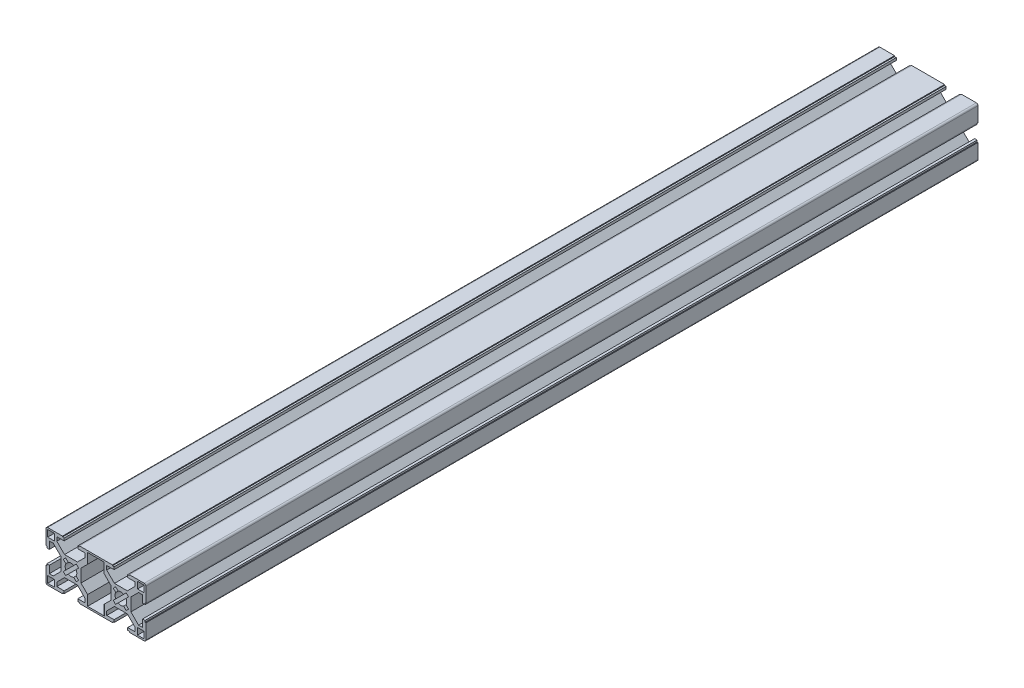
SolidWorks part; units mm, degrees
material "6063-O"
ref_plane "Plano frontal" through (0, 0, 0) normal (0, 0, 1) x (1, 0, 0)
ref_plane "Plano superior" through (0, 0, 0) normal (0, 1, 0) x (1, 0, 0)
ref_plane "Plano direito" through (0, 0, 0) normal (1, 0, 0) x (0, 0, -1)
sketch "Esboço1" plane through (0, 0, 0) normal (0, 0, 1) x (1, 0, 0)
  line L5 (0, 0) -> (-17.7944, 17.7944) construction
  line L6 (0, 3.5) -> (0, 6)
  line L8 (0, 6) -> (-3.8787, 6)
  line L9 (-3.5, 0) -> (-6, 0)
  line L48 (-6, 0) -> (-6, 3.8787)
  line L49 (-3.8787, 6) -> (-8.5, 10.6213)
  line L50 (-6, 3.8787) -> (-10.6213, 8.5)
  line L51 (0, 0) -> (-12.921, 0) construction
  line L52 (-8.5, 13) -> (-4.1, 13)
  line L53 (-4.1, 13) -> (-4.1, 14.5)
  line L54 (-4.1, 14.5) -> (-5.1, 14.5)
  line L55 (-5.1, 14.5) -> (-5.1, 15)
  line L56 (-5.1, 15) -> (-15, 15)
  line L57 (-15, 5.1) -> (-15, 15)
  line L58 (-14.5, 5.1) -> (-15, 5.1)
  line L59 (-14.5, 4.1) -> (-14.5, 5.1)
  line L60 (-13, 4.1) -> (-14.5, 4.1)
  line L61 (-13, 8.5) -> (-13, 4.1)
  line L62 (-1.6646, 3.0788) -> (-3.182, 4.5962)
  line L63 (-3.0788, 1.6646) -> (-4.5962, 3.182)
  line L64 (-4.5962, 3.182) -> (-3.182, 4.5962)
  line L65 (-8.5, 13) -> (-8.5, 10.6213)
  line L66 (-10, 14) -> (-14, 14)
  line L67 (-10, 14) -> (-10, 10)
  line L68 (-10, 10) -> (-14, 10)
  line L69 (-14, 14) -> (-14, 10)
  line L70 (-10, 14) -> (-14, 10) construction
  line L71 (-10, 10) -> (-14, 14) construction
  line L72 (-13, 8.5) -> (-10.6213, 8.5)
  circle A1 centre (0, 0) radius 3.5
  point P25 (-12, 12)
  dimension "D5" = 10.9
  dimension "D9" = 5.5
  dimension "D10" = 2
  dimension "D11" = 4
  dimension "D12" = 4
  dimension "D13" = 1
  dimension "D1" = 7
  dimension "D2" = 6
  dimension "D3" = 3
  dimension "D4" = 9.9
  dimension "D6" = 0.5
  dimension "D7" = 1.5
  dimension "D8" = 15
  dimension "D14" = 6.5
extrude "Ressalto-extrusão1" add sketch "Esboço1" along normal blind 500 contours A1 L6 L8 L49 L65 L52 L53 L54 L55 L56 L57 L58 L59 L60 L61 L72 L50 L48 L9 L63 L64 L62 L69 L66 L67 L68
sketch "Esboço3" plane through (0, 0, 0) normal (1, 0, 0) x (0, 0, -1)
  line L0 (0, 0) -> (-1000, 0) construction
  dimension "D1" = 1000
pattern_circular "PadrãoCircular1" count 4 every 90 about axis through (0, 0, 0) along (0, 0, 1) of "Ressalto-extrusão1"
pattern_linear "Padrão linear1" count 2 spacing 30 along (1, 0, 0) of "Ressalto-extrusão1", "PadrãoCircular1"
sketch "Esboço4" plane through (0, 0, 0) normal (0, 0, -1) x (-1, 0, 0)
  line L0 (-20, 14) -> (-20, -14)
  line L1 (-20, -14) -> (-10, -14)
  line L2 (-10, -14) -> (-10, 14)
  line L3 (-10, 14) -> (-20, 14)
extrude "Corte-extrusão1" cut sketch "Esboço4" against normal through all
fillet "Filete1" radius 1 4 edges at (45, -15, 250) (45, 15, 250) (-15, 15, 250) (-15, -15, 250)
ref_plane "Plane1" through (0, 0, 250) normal (0, 0, -1) x (-1, 0, 0)
ref_plane "Plane2" through (15, 0, 0) normal (-1, 0, 0) x (0, 0, 1)
